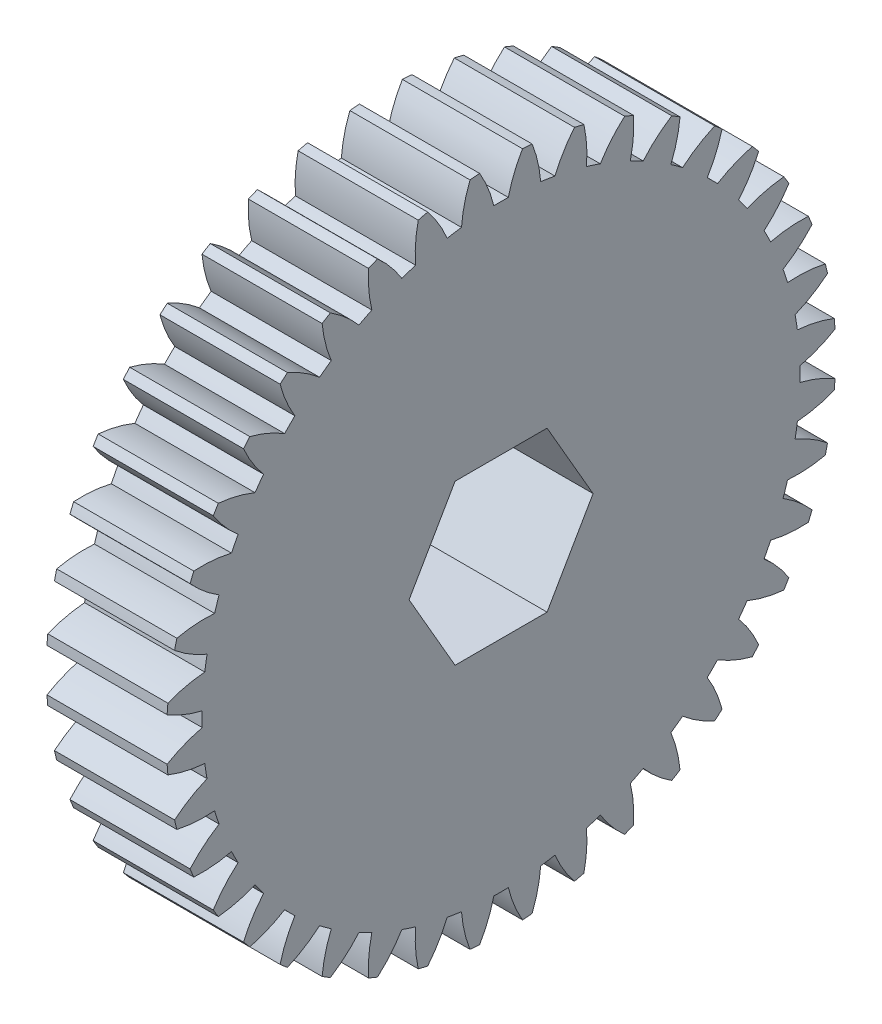
SolidWorks part; units mm, degrees
material "6061 Alloy"
ref_plane "Plane1" through (0, 0, 0) normal (0, 0, 1) x (1, 0, 0)
ref_plane "Plane2" through (0, 0, 0) normal (0, 1, 0) x (1, 0, 0)
ref_plane "Plane3" through (0, 0, 0) normal (1, 0, 0) x (0, 0, -1)
sketch "HoldingSke" plane through (0, 0, 0) normal (0, 1, 0) x (1, 0, 0)
  line L0 (0, 0) -> (389.1506, -326.5361)
  line L1 (-15, 0) -> (100, 0) construction
  line L2 (0, 0) -> (-2.1039, 2.3779)
  line L3 (0, 0) -> (-11.863, 4.5341)
  line L4 (0, 0) -> (6.6156, 5.5511)
  line L5 (0, 0) -> (-9.5432, -3.5593)
  line L6 (0, 0) -> (-7.938, -5.3558)
  line L7 (-2.1039, 2.3779) -> (0.0885, 12.3246)
  line L8 (-76.2, 54.61) -> (-61.976, 54.61)
  line L9 (-71.009, 38.7566) -> (-53.1078, 45.2721)
  line L10 (-76.2, 71.12) -> (104.1128, 71.12)
  line L11 (0, 0) -> (-9.5758, 0)
  line L12 (-76.2, 101.6) -> (-76.1492, 101.6)
  line L13 (24.9733, 27.94) -> (52.9518, 28.4284)
  line L14 (24.9733, 27.94) -> (25.0241, 27.9398)
  line L15 (24.9733, 27.94) -> (100.4021, 29.52)
  circle A0 centre (0, 0) radius 6.35
  circle A1 centre (0, 0) radius 8.9281
  circle A2 centre (0, 0) radius 8.9281
  circle A3 centre (0, 0) radius 6.35
  dimension "MHD" = 17.8562
  dimension "Hub_dia" = 17.8562
  dimension "Bore" = 12.7
  dimension "MBD" = 12.7
  dimension "Num_teeth" = 40
  dimension "Pitch_radius" = 180.3128
  dimension "Pitch" = 508
  dimension "Width" = 9.5758
  dimension "Overall_len" = 10.1854
  dimension "Show_teeth" = 40
  dimension "Thickness" = 9.5758
  dimension "OAL" = 10.1855
  dimension "T_dim" = 14.224
  dimension "Ap" = 20
  dimension "H" = 19.05
  dimension "Backlash" = 0.0508
  dimension "Addendum_fac" = 1
  dimension "Dedendum_fac" = 1.2
  dimension "Clearance_fac" = 0.2
  dimension "Dedendum_add" = 0.0508
sketch "BasProSke" plane through (0, 0, 0) normal (0, 1, 0) x (1, 0, 0)
  line L0 (-10, 0) -> (60, 0) construction
  line L1 (0, 0) -> (0, 26.67)
  line L2 (0, 0) -> (9.5758, 0)
  line L3 (9.5758, 0) -> (9.5758, 26.67)
  line L4 (9.5758, 26.67) -> (0, 26.67)
  dimension "Diameter" = 53.34
  dimension "Thickness" = 9.5758
revolve "Base-Revolve" add sketch "BasProSke" angle 360 about L0
sketch "TooCutSke" plane through (0, 0, 0) normal (1, 0, 0) x (0, 0, -1)
  line L1 (0, 0) -> (0, 107) construction
  line L2 (0, 0) -> (-1.0861, 25.3768) construction
  line L3 (0, 0) -> (-3.9832, 50.611) construction
  line L4 (-1.0861, 25.3768) -> (-1.9916, 25.3055) construction
  arc A0 (0.5773, 23.8182) -> (-0.5773, 23.8182) centre (0, 0) ccw
  arc A1 (1.7213, 26.6399) -> (-1.7213, 26.6399) centre (0, 0) ccw
  circle A2 centre (0, 0) radius 25.4 construction
  circle A3 centre (0, 0) radius 23.8682 construction
  arc A4 (-0.5773, 23.8182) -> (-1.7213, 26.6399) centre (-10.4586, 21.4548) ccw
  arc A5 (1.7213, 26.6399) -> (0.5773, 23.8182) centre (10.4586, 21.4548) ccw
  dimension "Root_dia" = 47.6504
  dimension "Overcut_dia" = 53.3908
  dimension "Pitch_dia" = 50.8
  dimension "Base_dia" = 47.7364
  dimension "Flank_rad" = 10.16
  dimension "Half_ang" = 4.5
  dimension "Half_CT" = 0.9083
extrude "ToothCut" cut sketch "TooCutSke" along normal through all
fillet "Breaks" [suppressed] radius 0.0254
fillet "RootFillets" [suppressed] radius 0.3048
pattern_circular "TeethCuts" count 40 every 9 about axis through (-10, 0, 0) along (1, 0, 0) of "ToothCut", "RootFillets", "Breaks"
sketch "HubNeaOneSke" plane through (0, 0, 0) normal (-1, 0, 0) x (0, 0, 1)
  circle A0 centre (0, 0) radius 8.9281
  dimension "Diameter" = 17.8562
extrude "HubNearOne" add sketch "HubNeaOneSke" along normal blind 0.6097
sketch "HubNeaBotSke" plane through (0, 0, 0) normal (-1, 0, 0) x (0, 0, 1)
  circle A0 centre (0, 0) radius 8.9281
  dimension "Diameter" = 17.8562
extrude "HubNearBoth" [suppressed] add sketch "HubNeaBotSke" along normal blind 0.3048
ref_plane "FarPln" through (9.5758, 0, 0) normal (1, 0, 0) x (0, 0, -1)
sketch "HubFarSke" plane through (9.5758, 0, 0) normal (1, 0, 0) x (0, 0, -1)
  circle A0 centre (0, 0) radius 8.9281
  dimension "Diameter" = 17.8562
extrude "HubFar" [suppressed] add sketch "HubFarSke" along normal blind 0.3048
sketch "BorSke" plane through (0, 0, 0) normal (1, 0, 0) x (0, 0, -1)
  circle A0 centre (0, 0) radius 6.35
  dimension "Diameter" = 12.7
extrude "Bore" cut sketch "BorSke" along normal mid plane 20.3709
sketch "KeySke" plane through (0, 0, 0) normal (1, 0, 0) x (0, 0, -1)
  line L0 (-1.5875, 0) -> (-1.5875, 7.874)
  line L1 (-1.5875, 7.874) -> (1.5875, 7.874)
  line L2 (1.5875, 7.874) -> (1.5875, 0)
  line L3 (0, 0) -> (0, 34) construction
  line L4 (-1.5875, 0) -> (1.5875, 0)
  dimension "Offset" = 7.874
  dimension "Width" = 3.175
extrude "Keyway" [suppressed] cut sketch "KeySke" along normal mid plane 20.3709
pattern_circular "Keyway2" [suppressed] count 2 every 90 about axis through (-10, 0, 0) along (1, 0, 0)
sketch "Sketch1" plane through (9.5758, 0, 0) normal (1, 0, 0) x (0, 0, -1)
  line L1 (3.6662, 6.35) -> (-3.6662, 6.35)
  line L2 (-3.6662, 6.35) -> (-7.3323, 0)
  line L3 (-7.3323, 0) -> (-3.6662, -6.35)
  line L4 (-3.6662, -6.35) -> (3.6662, -6.35)
  line L5 (3.6662, -6.35) -> (7.3323, 0)
  line L6 (7.3323, 0) -> (3.6662, 6.35)
  circle A0 centre (0, 0) radius 6.35 construction
  dimension "D1" = 12.7
extrude "Cut-Extrude1" cut sketch "Sketch1" against normal through all
equation "' \"Pitch@HoldingSke\" = 4"
equation "' \"Num_teeth@HoldingSke\" = 12"
equation "' \"Ap@HoldingSke\" =  20"
equation "' \"Width@HoldingSke\" = 0.5"
equation "' \"Hub_dia@HoldingSke\"= 1"
equation "' \"Overall_len@HoldingSke\" = 1.0"
equation "' \"Bore@HoldingSke\" = 0.75"
equation "' \"T_dim@HoldingSke\" = 0.85"
equation "' \"Width@KeySke\" = 0.25"
equation "' \"Show_teeth@HoldingSke\" = 13"
equation "' \"Backlash@HoldingSke\" = 0.009"
equation "' \"Addendum_fac@HoldingSke\" = 1.0"
equation "' \"Dedendum_fac@HoldingSke\" = 1.25"
equation "' \"Dedendum_add@HoldingSke\" = 0.00005"
equation "' \"Clearance_fac@HoldingSke\" = 0.25"
equation "' \"Pitch@HoldingSke\" = 0.5"
equation "' \"Num_teeth@HoldingSke\" = 23"
equation "' \"Show_teeth@HoldingSke\" = 23"
equation "' \"Backlash@HoldingSke\" = 0.0375"
equation "\"Overcut_dia@TooCutSke\" = (\"Num_teeth@HoldingSke\" + 2 * \"Addendum_fac@HoldingSke\") / \"Pitch@HoldingSke\" + 0.002"
equation "\"Pitch_dia@TooCutSke\" = \"Num_teeth@HoldingSke\" / \"Pitch@HoldingSke\""
equation "\"Base_dia@TooCutSke\" = \"Num_teeth@HoldingSke\" / \"Pitch@HoldingSke\" * cos((\"Ap@HoldingSke\"  * 3.14159265 / 180))"
equation "\"Root_dia@TooCutSke\" = (\"Num_teeth@HoldingSke\" + 2) / \"Pitch@HoldingSke\" - 2 * (\"Addendum_fac@HoldingSke\" + \"Dedendum_fac@HoldingSke\") / \"Pitch@HoldingSke\" - \"Dedendum_add@HoldingSke\" * 2"
equation "\"Half_ang@TooCutSke\" = 180 / \"Num_teeth@HoldingSke\""
equation "\"Half_CT@TooCutSke\" = \"Num_teeth@HoldingSke\" / \"Pitch@HoldingSke\" * sin((3.14159265 / 2 / \"Num_teeth@HoldingSke\")) / 2 - 7 * \"Backlash@HoldingSke\" / 4"
equation "\"Flank_rad@TooCutSke\" = \"Num_teeth@HoldingSke\" / \"Pitch@HoldingSke\" / 5"
equation "\"Radius@RootFillets\" = \"Clearance_fac@HoldingSke\" / \"Pitch@HoldingSke\" + \"Dedendum_add@HoldingSke\""
equation "\"Break_rad@Breaks\" = 0.02 / \"Pitch@HoldingSke\""
equation "\"Thickness@HoldingSke\" = \"Width@HoldingSke\""
equation "\"OAL@HoldingSke\" = \"Thickness@HoldingSke\""
equation "\"MHD@HoldingSke\" = (\"Num_teeth@HoldingSke\" + 2) / \"Pitch@HoldingSke\" - 2 * (\"Addendum_fac@HoldingSke\" + \"Dedendum_fac@HoldingSke\")  / \"Pitch@HoldingSke\" - \"Dedendum_add@HoldingSke\" * 2"
equation "\"MBD@HoldingSke\" = (\"Num_teeth@HoldingSke\" + 2) / \"Pitch@HoldingSke\" - 2 * (\"Addendum_fac@HoldingSke\" + \"Dedendum_fac@HoldingSke\")  / \"Pitch@HoldingSke\" - \"Dedendum_add@HoldingSke\" * 2 - 0.002"
equation "\"MHD@HoldingSke\" = ((sgn( \"MHD@HoldingSke\" - \"Hub_dia@HoldingSke\" )-1)*( \"MHD@HoldingSke\" - \"Hub_dia@HoldingSke\" ))/-2+ \"Hub_dia@HoldingSke\""
equation "\"MBD@HoldingSke\" = ((sgn( \"MBD@HoldingSke\" - \"Bore@HoldingSke\" )-1)*( \"MBD@HoldingSke\" - \"Bore@HoldingSke\" ))/-2+ \"Bore@HoldingSke\""
equation "\"OAL@HoldingSke\" = ((sgn( \"OAL@HoldingSke\" - \"Overall_len@HoldingSke\" )+1)*( \"OAL@HoldingSke\" - \"Overall_len@HoldingSke\" ))/2 + \"Overall_len@HoldingSke\" + 0.000002"
equation "\"Num_teeth@TeethCuts\" = int( \"Show_teeth@HoldingSke\" ) + 1"
equation "\"Num_teeth@TeethCuts\" = ((sgn( \"Num_teeth@TeethCuts\" - \"Num_teeth@HoldingSke\" )-1)*( \"Num_teeth@TeethCuts\" - \"Num_teeth@HoldingSke\" ))/-2+ \"Num_teeth@HoldingSke\""
equation "\"Num_teeth@TeethCuts\" = ((sgn( \"Num_teeth@TeethCuts\" - 2.0)+1)*( \"Num_teeth@TeethCuts\" - 2.0))/2 +2.0"
equation "\"Angle@TeethCuts\" = 360.0 / \"Num_teeth@HoldingSke\""
equation "\"Diameter@BasProSke\" = (\"Num_teeth@HoldingSke\" + 2 * \"Addendum_fac@HoldingSke\") / \"Pitch@HoldingSke\""
equation "\"Thickness@BasProSke\"  = \"Thickness@HoldingSke\""
equation "' \"Fillet_rad@BasProSke\" =  \"Thickness@HoldingSke\" * 0.05"
equation "\"MHD@HoldingSke\" = ((sgn( \"MHD@HoldingSke\" - \"Root_dia@TooCutSke\" )-1)*( \"MHD@HoldingSke\" - \"Root_dia@TooCutSke\" ))/-2+ \"Root_dia@TooCutSke\""
equation "\"Diameter@HubNeaOneSke\" = \"MHD@HoldingSke\""
equation "\"Length@HubNearOne\" = \"OAL@HoldingSke\" - \"Thickness@BasProSke\""
equation "\"Diameter@HubNeaBotSke\" = \"MHD@HoldingSke\""
equation "\"Length@HubNearBoth\" = ( \"OAL@HoldingSke\" - \"Thickness@BasProSke\" ) / 2.0"
equation "\"Thickness@FarPln\" = \"Thickness@BasProSke\""
equation "\"Diameter@HubFarSke\" = \"MHD@HoldingSke\""
equation "\"Length@HubFar\" = ( \"OAL@HoldingSke\" - \"Thickness@BasProSke\" ) / 2.0"
equation "\"Diameter@BorSke\" = \"MBD@HoldingSke\""
equation "\"D1@Bore\" = \"OAL@HoldingSke\" * 2.0"
equation "\"D1@Keyway\" = \"OAL@HoldingSke\" * 2.0"
equation "\"Offset@KeySke\" = \"T_dim@HoldingSke\" - \"MBD@HoldingSke\" / 2.0"
